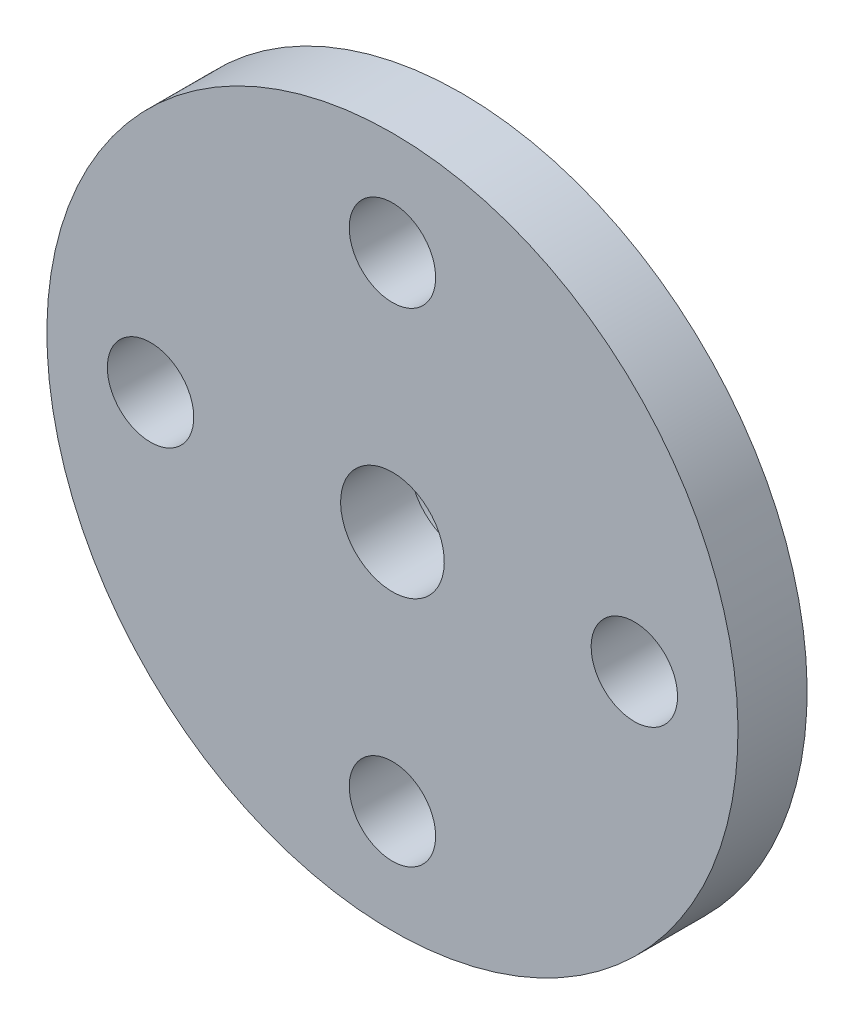
SolidWorks part; units mm, degrees
ref_plane "前视基准面" through (0, 0, 0) normal (0, 0, 1) x (1, 0, 0)
ref_plane "上视基准面" through (0, 0, 0) normal (0, 1, 0) x (1, 0, 0)
ref_plane "右视基准面" through (0, 0, 0) normal (1, 0, 0) x (0, 0, -1)
sketch "草图2" plane through (0, 0, 0) normal (1, 0, 0) x (0, 0, -1)
  line L0 (0, 0) -> (-50000, 0) construction
  line L1 (0, 0) -> (0, 50000) construction
  line L2 (-2, 1.5) -> (-2, 10)
  line L3 (-2, 10) -> (0, 10)
  line L4 (0, 10) -> (0, 5)
  line L5 (0, 5) -> (3.5, 5)
  line L6 (3.5, 5) -> (3.5, 3)
  line L7 (3.5, 3) -> (0, 3)
  line L8 (0, 3) -> (0, 1.5)
  line L9 (0, 1.5) -> (-2, 1.5)
  dimension "D1" = 1.5
  dimension "D2" = 5
  dimension "D3" = 3
  dimension "D4" = 2
  dimension "D5" = 10
  dimension "D6" = 2
  dimension "D7" = 3.5
revolve "旋转1" add sketch "草图2" angle 360 about L0
hole_wizard "M3 螺纹孔1" positions "3D草图1" profile "草图4" tap size "M3" standard "GB"
sketch3d "3D草图1"
  point P0 (0, 7, 2)
sketch "草图4" plane through (0, 7, 2) normal (1, 0, 0) x (0, -1, 0)
  line L0 (0, 0) -> (0, 8.2511)
  line L1 (0, 8.2511) -> (1.25, 7.5)
  line L2 (1.25, 7.5) -> (1.25, 0)
  line L5 (1.25, 0) -> (0, 0)
  line L10 (0, 8.2511) -> (-1.25, 7.5) construction
  line L11 (0, -6.35) -> (0, 107.95) construction
  dimension "螺纹孔钻头直径" = 2.5
  dimension "螺纹孔钻头深度" = 7.5
  dimension "导头角度" = 118
cosmetic thread "孔螺蚊线1" parameters "D1"=5.5, "D2"=3
pattern_circular "阵列(圆周)1" count 4 every 90 about axis through (0, 0, 0) along (0, 0, 1) of "M3 螺纹孔1"
